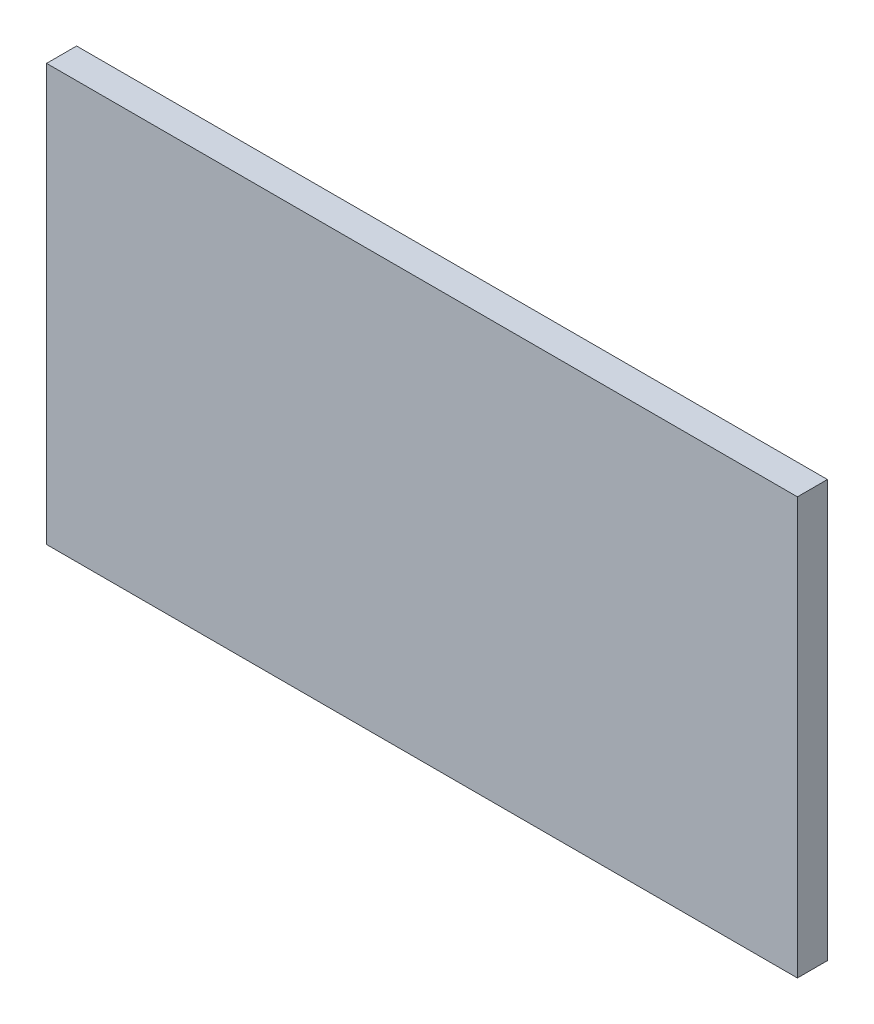
SolidWorks part; units mm, degrees
material "Plain Carbon Steel"
ref_plane "Front Plane" through (0, 0, 0) normal (0, 0, 1) x (1, 0, 0)
ref_plane "Top Plane" through (0, 0, 0) normal (0, 1, 0) x (1, 0, 0)
ref_plane "Right Plane" through (0, 0, 0) normal (1, 0, 0) x (0, 0, -1)
sketch "Sketch1" plane through (0, 0, 0) normal (0, 0, 1) x (1, 0, 0)
  line L0 (250, 0) -> (-250, 0) construction
  line L1 (-500, 5) -> (500, 5)
  line L2 (-500, 5) -> (-500, -550)
  line L3 (-500, -550) -> (500, -550)
  line L4 (500, 5) -> (500, -550)
  point P6 (0, 5)
  dimension "D1" = 5
  dimension "D2" = 1000
  dimension "D3" = 555
extrude "Boss-Extrude1" add sketch "Sketch1" along normal blind 40 contours L2 L3 L4 L1
